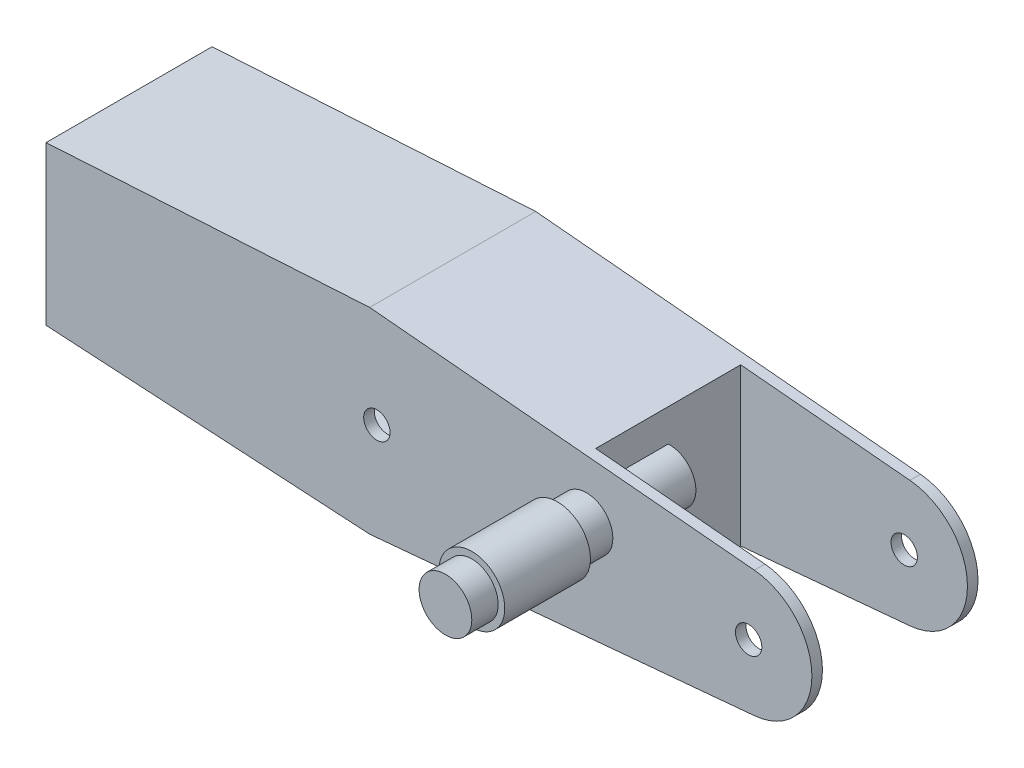
SolidWorks part; units mm, degrees
ref_plane "Plan de face" through (0, 0, 0) normal (0, 0, 1) x (1, 0, 0)
ref_plane "Plan de dessus" through (0, 0, 0) normal (0, 1, 0) x (1, 0, 0)
ref_plane "Plan de droite" through (0, 0, 0) normal (1, 0, 0) x (0, 0, -1)
sketch "Esquisse1" plane through (0, 0, 0) normal (0, 0, 1) x (1, 0, 0)
  line L0 (-298.4832, 0) -> (378.7158, 0) construction
  line L1 (-251, 60) -> (-251, -60)
  line L2 (-251, 60) -> (-5.4786, 74.5)
  line L3 (-5.4786, 74.5) -> (286.3729, 47.8004)
  line L4 (-5.4786, -74.5) -> (286.3729, -47.8004)
  line L5 (-251, -60) -> (-5.4786, -74.5)
  arc A0 (286.3729, -47.8004) -> (286.3729, 47.8004) centre (282, 0) ccw
  point P13 (-251, 0)
  dimension "D1" = 96
  dimension "D2" = 282
  dimension "D3" = 251
  dimension "D4" = 74.5
  dimension "D5" = 60
extrude "Extrusion1" add sketch "Esquisse1" along normal blind 126
ref_plane "Plan1" through (158, 0, 0) normal (1, 0, 0) x (0, 0, -1)
sketch "Esquisse2" plane through (158, 0, 0) normal (1, 0, 0) x (0, 0, -1)
  line L0 (-63, 78.713) -> (-63, -83.3706) construction
  line L2 (-118, 40) -> (-8, 40)
  line L3 (-118, 40) -> (-118, -100)
  line L4 (-118, -100) -> (-8, -100)
  line L5 (-8, 40) -> (-8, -100)
  dimension "D1" = 63
  dimension "D2" = 55
  dimension "D3" = 110
  dimension "D4" = 100
  dimension "D5" = 40
extrude "Enlèv. mat.-Extru.1" cut sketch "Esquisse2" along normal blind 200
ref_plane "Plan2" through (0, 0, 63) normal (0, 0, 1) x (1, 0, 0)
sketch "Esquisse6" plane through (0, 0, 63) normal (0, 0, 1) x (1, 0, 0)
  line L0 (-251, 60) -> (-251, -60) construction
  line L1 (-251, -60) -> (-5.4786, -74.5) construction
  line L2 (-5.4786, -74.5) -> (286.3729, -47.8004) construction
  line L3 (286.3729, 47.8004) -> (-5.4786, 74.5) construction
  line L4 (-5.4786, 74.5) -> (-251, 60) construction
  line L5 (-251, 60) -> (-251, -60)
  line L6 (-251, -60) -> (-5.4786, -74.5)
  line L7 (-5.4786, -74.5) -> (158, -59.5444)
  line L8 (158, 59.5444) -> (-5.4786, 74.5)
  line L9 (-5.4786, 74.5) -> (-251, 60)
  line L10 (158, 40) -> (158, -59.5444) construction
  line L11 (158, 59.5444) -> (158, -59.5444)
  line L12 (152, 54.0682) -> (152, -54.0682)
  line L13 (-5.5756, -68.4838) -> (152, -54.0682)
  line L14 (-245, -54.3439) -> (-5.5756, -68.4838)
  line L15 (-245, 54.3439) -> (-245, -54.3439)
  line L16 (-5.5756, 68.4838) -> (-245, 54.3439)
  line L17 (152, 54.0682) -> (-5.5756, 68.4838)
  dimension "D1" = 6
extrude "Enlèv. mat.-Extru.2" cut sketch "Esquisse6" against normal blind 55 and the other way blind 55 flip side to cut
sketch "Esquisse8" plane through (0, 0, 63) normal (0, 0, 1) x (1, 0, 0)
  circle A0 centre (159, 15) radius 20
  dimension "D3" = 40
  dimension "D1" = 159
  dimension "D2" = 15
extrude "Extrusion2" add sketch "Esquisse8" along normal blind 85
sketch "Esquisse9" plane through (0, 0, 148) normal (0, 0, 1) x (1, 0, 0)
  circle A0 centre (159, 15) radius 25
  circle A1 centre (159, 15) radius 20 construction
  dimension "D1" = 50
extrude "Extrusion3" add sketch "Esquisse9" along normal blind 65
sketch "Esquisse10" plane through (0, 0, 213) normal (0, 0, 1) x (1, 0, 0)
  circle A0 centre (159, 15) radius 20
  circle A1 centre (159, 15) radius 25 construction
  dimension "D1" = 40
extrude "Extrusion4" add sketch "Esquisse10" along normal blind 20
sketch "Esquisse11" plane through (0, 0, 126) normal (0, 0, 1) x (1, 0, 0)
  circle A0 centre (282, 0) radius 10
  arc A1 (286.3729, -47.8004) -> (286.3729, 47.8004) centre (282, 0) ccw construction
  dimension "D1" = 20
extrude "Enlèv. mat.-Extru.3" cut sketch "Esquisse11" against normal through all
sketch "Esquisse12" plane through (0, 0, 126) normal (0, 0, 1) x (1, 0, 0)
  circle A0 centre (0, 0) radius 10
  dimension "D1" = 20
extrude "Enlèv. mat.-Extru.4" cut sketch "Esquisse12" against normal through all
